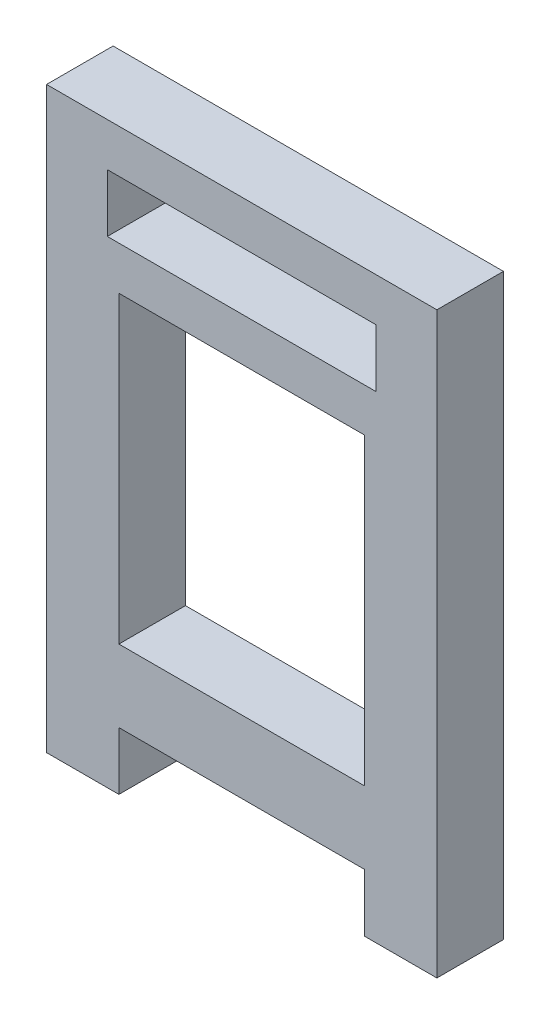
SolidWorks part; units mm, degrees
ref_plane "Front Plane" through (0, 0, 0) normal (0, 0, 1) x (1, 0, 0)
ref_plane "Top Plane" through (0, 0, 0) normal (0, 1, 0) x (1, 0, 0)
ref_plane "Right Plane" through (0, 0, 0) normal (1, 0, 0) x (0, 0, -1)
sketch "Sketch1" plane through (0, 0, 0) normal (0, 0, 1) x (1, 0, 0)
  line L0 (0, 0) -> (0, -2)
  line L1 (2.5, 0) -> (10.99, 0)
  line L2 (0, 0) -> (0, 18)
  line L3 (0, 18) -> (13.49, 18)
  line L4 (13.49, 0) -> (13.49, 18)
  line L5 (0, -2) -> (2.5, -2)
  line L6 (2.5, -2) -> (2.5, 0)
  line L7 (13.49, 0) -> (13.49, -2)
  line L8 (13.49, -2) -> (10.99, -2)
  line L9 (10.99, -2) -> (10.99, 0)
  line L12 (2.5, 2.5) -> (10.99, 2.5)
  line L13 (2.5, 2.5) -> (2.5, 13)
  line L14 (2.5, 13) -> (10.99, 13)
  line L15 (10.99, 2.5) -> (10.99, 13)
  line L16 (2.1, 14.5) -> (11.39, 14.5)
  line L17 (2.1, 14.5) -> (2.1, 16.5)
  line L18 (2.1, 16.5) -> (11.39, 16.5)
  line L19 (11.39, 14.5) -> (11.39, 16.5)
  dimension "D1" = 18
  dimension "D2" = 2.5
  dimension "D3" = 8.49
  dimension "D4" = 2
  dimension "D5" = 2
  dimension "D6" = 2.5
  dimension "D7" = 2.5
  dimension "D8" = 10.5
  dimension "D9" = 2
  dimension "D10" = 1.5
  dimension "D12" = 0.4
extrude "Boss-Extrude1" add sketch "Sketch1" along normal blind 2.3
